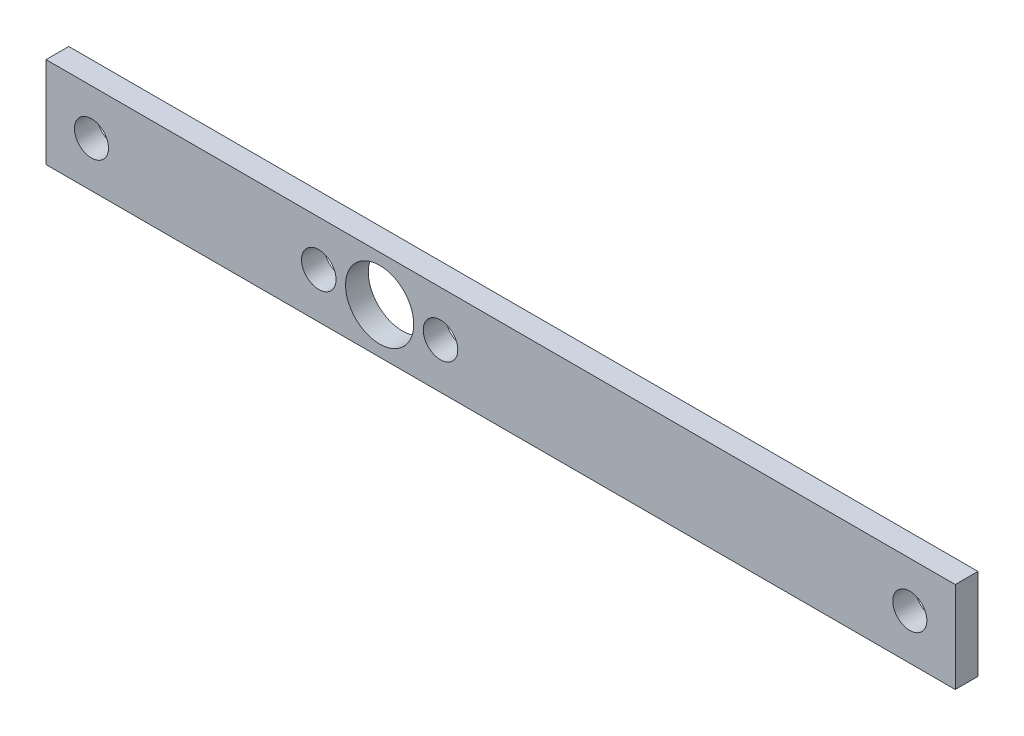
SolidWorks part; units mm, degrees
ref_plane "Front Plane" through (0, 0, 0) normal (0, 0, 1) x (1, 0, 0)
ref_plane "Top Plane" through (0, 0, 0) normal (0, 1, 0) x (1, 0, 0)
ref_plane "Right Plane" through (0, 0, 0) normal (1, 0, 0) x (0, 0, -1)
sketch "Sketch1" plane through (0, 0, 0) normal (0, 0, 1) x (1, 0, 0)
  line L1 (0, 0) -> (127, 0)
  line L2 (0, 0) -> (0, 12.7)
  line L3 (0, 12.7) -> (127, 12.7)
  line L4 (127, 0) -> (127, 12.7)
  circle A0 centre (38.1, 6.35) radius 2.413
  circle A1 centre (55.1, 6.35) radius 2.413
  circle A2 centre (6.35, 6.35) radius 2.3813
  circle A3 centre (120.65, 6.35) radius 2.3813
  circle A4 centre (46.6, 6.35) radius 4.7625
  point P15 (0, 0)
  dimension "D3" = 4.826
  dimension "D4" = 4.826
  dimension "D5" = 6.35
  dimension "D6" = 6.35
  dimension "D7" = 8.5
  dimension "D8" = 38.1
  dimension "D9" = 4.7625
  dimension "D10" = 6.35
  dimension "D11" = 6.35
  dimension "D12" = 4.7625
  dimension "D13" = 6.35
  dimension "D14" = 6.35
  dimension "D15" = 9.525
  dimension "D16" = 6.35
  dimension "D17" = 8.5
  dimension "D1" = 12.7
  dimension "D2" = 127
other "AlignGroup1"
extrude "Boss-Extrude1" add sketch "Sketch1" along normal blind 3.175
